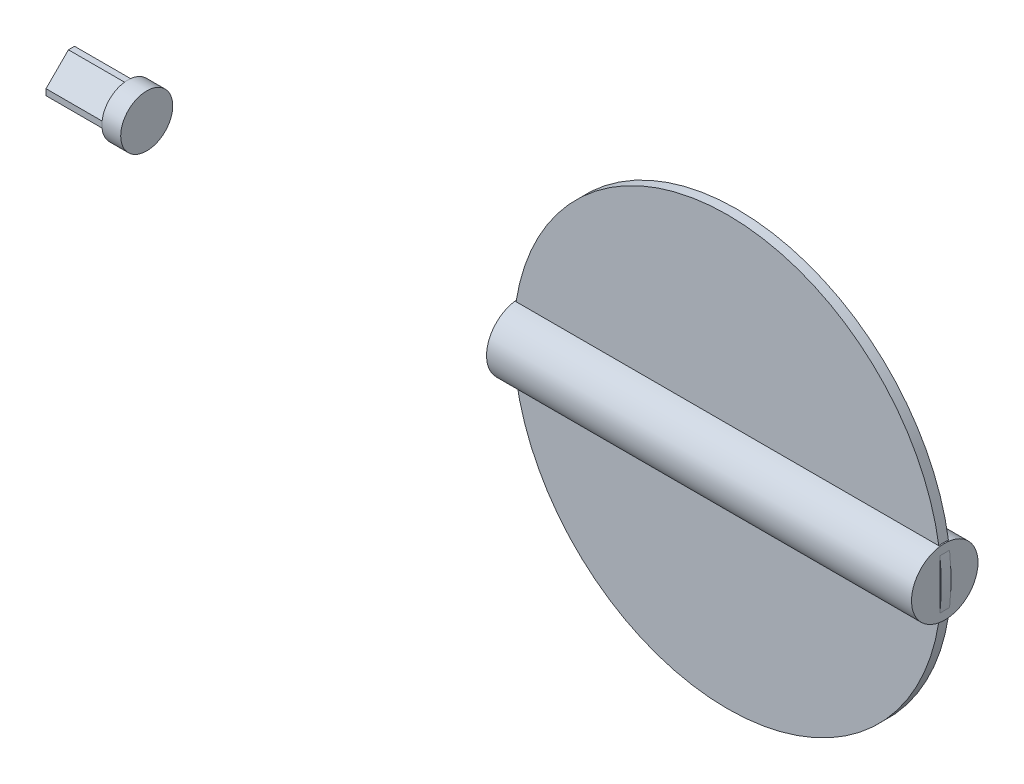
SolidWorks part; units mm, degrees
ref_plane "Front Plane" through (0, 0, 0) normal (0, 0, 1) x (1, 0, 0)
ref_plane "Top Plane" through (0, 0, 0) normal (0, 1, 0) x (1, 0, 0)
ref_plane "Right Plane" through (0, 0, 0) normal (1, 0, 0) x (0, 0, -1)
sketch "Sketch1" plane through (0, 0, 0) normal (0, 0, 1) x (1, 0, 0)
  circle A0 centre (0, 0) radius 74
extrude "HOLT disc - 148 mm diameter and 3.33 mm thick" add sketch "Sketch1" along normal blind 3.33 from offset 1.665
sketch "Sketch2" plane through (0, 0, 0) normal (1, 0, 0) x (0, 0, -1)
  circle A0 centre (0, 0) radius 11.5
extrude "Visible stem - 23 mm diameter with running clearance" add sketch "Sketch2" along normal blind 147 from offset 73.5
sketch "Sketch3" plane through (0, 0, 0) normal (1, 0, 0) x (0, 0, -1)
  circle A0 centre (0, 0) radius 9
extrude "Upper stem collar at valve flange" add sketch "Sketch3" along normal blind 6.52 from offset 209.0719
sketch "Sketch4" plane through (0, 0, 0) normal (1, 0, 0) x (0, 0, -1)
  line L0 (-8.82, 1.06) -> (-8.82, -1.06)
  line L1 (-8.82, -1.06) -> (-1.06, -8.82)
  line L2 (-1.06, -8.82) -> (1.06, -8.82)
  line L3 (1.06, -8.82) -> (8.82, -1.06)
  line L4 (8.82, -1.06) -> (8.82, 1.06)
  line L5 (8.82, 1.06) -> (1.06, 8.82)
  line L6 (1.06, 8.82) -> (-1.06, 8.82)
  line L7 (-1.06, 8.82) -> (-8.82, 1.06)
extrude "HOLT 14 mm square drive with corner flats" add sketch "Sketch4" along normal blind 19.5 from offset 228.5719
